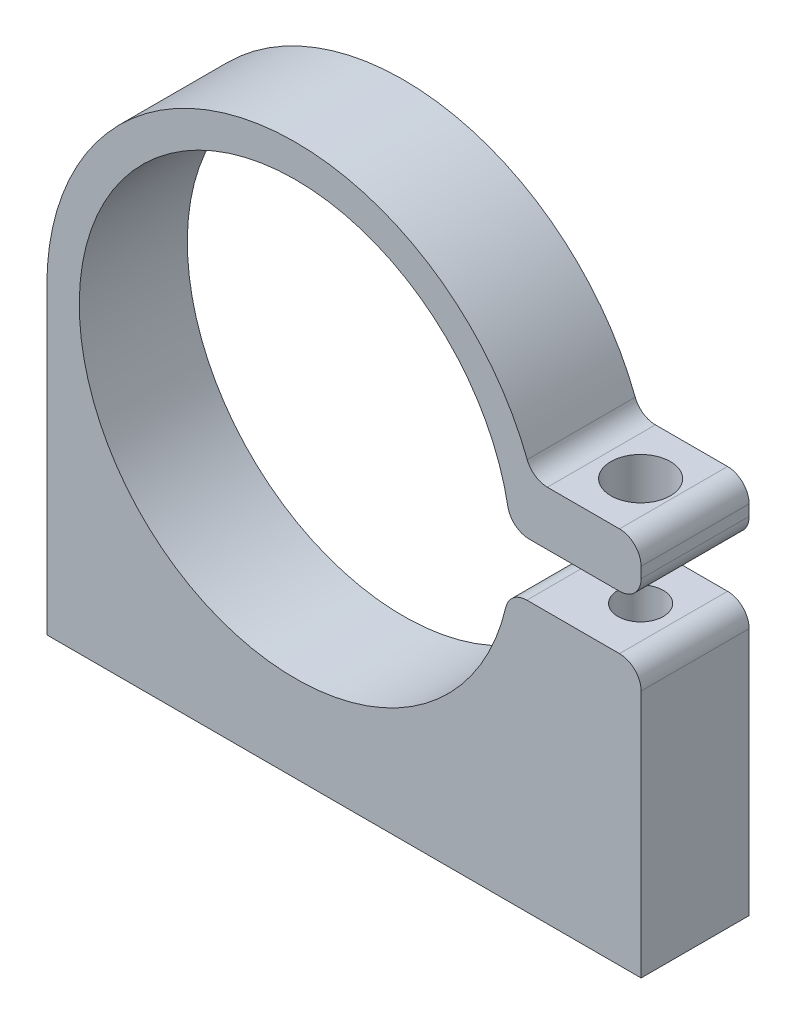
SolidWorks part; units mm, degrees
material "Сплав 2024"
ref_plane "Спереди" through (0, 0, 0) normal (0, 0, 1) x (1, 0, 0)
ref_plane "Сверху" through (0, 0, 0) normal (0, 1, 0) x (1, 0, 0)
ref_plane "Справа" through (0, 0, 0) normal (1, 0, 0) x (0, 0, -1)
sketch "Эскиз1" plane through (0, 0, 0) normal (0, 0, 1) x (1, 0, 0)
  line L0 (32, -3) -> (19.7737, -3)
  line L1 (19.8997, 2) -> (32, 2)
  line L2 (-23, 0) -> (-23, -28)
  line L3 (-23, -28) -> (32, -28)
  line L4 (32, -3) -> (32, -28)
  line L5 (32, 2) -> (32, 7)
  line L6 (32, 7) -> (21.9089, 7)
  arc A0 (19.8997, 2) -> (19.7737, -3) centre (0, 0) ccw
  arc A1 (21.9089, 7) -> (-23, 0) centre (0, 0) ccw
  circle A3 centre (0, 0) radius 23 construction
  circle A4 centre (0, 0) radius 20 construction
  point P4 (20.0824, 6.1398)
  point P12 (24, 0)
  dimension "D1" = 40
  dimension "D3" = 28
  dimension "D4" = 55
  dimension "D5" = 5
  dimension "D6" = 5
  dimension "D7" = 25
  dimension "D2" = 3
extrude "Бобышка-Вытянуть1" add sketch "Эскиз1" along normal blind 10
sketch "Эскиз2" plane through (0, 7, 0) normal (0, 1, 0) x (1, 0, 0)
  line L0 (26.9545, 0) -> (26.9545, -10) construction
  line L1 (32, -10) -> (32, 0) construction
  line L2 (32, -10) -> (21.9089, -10) construction
  line L3 (23.1247, -5) -> (32, -5) construction
fillet "Скругление1" radius 2 6 edges at (32, 2, 5) (32, 7, 5) (32, -3, 5) (19.7737, -3, 5) (19.8997, 2, 5) (21.9089, 7, 5)
hole_wizard "Отверстие с зазором M51" positions "Эскиз4" profile "Эскиз3" hole size "M5" standard "Ansi Metric"
sketch "Эскиз4" plane through (0, 7, 0) normal (0, 1, 0) x (1, 0, 0)
  line L0 (26.9545, 0) -> (26.9545, -10) construction
  point P0 (26.9545, -5)
sketch "Эскиз3" plane through (26.9545, 7, 5) normal (1, 0, 0) x (0, 0, 1)
  line L0 (0, 0) -> (0, 5)
  line L1 (0, 5) -> (2.75, 5)
  line L2 (2.75, 5) -> (2.75, 0)
  line L5 (2.75, 0) -> (0, 0)
  line L11 (0, -6.35) -> (0, 107.95) construction
  dimension "Диаметр сквозного отверстия" = 5.5
  dimension "Глубина сквозного отверстия" = 5
hole_wizard "Отверстие обработанное метчиком M5x0.81" positions "Эскиз6" profile "Эскиз5" tap size "M5x0.8" standard "Ansi Metric" end condition through all
sketch "Эскиз6" plane through (0, -3, 0) normal (0, 1, 0) x (1, 0, 0)
  line L0 (26.9545, 0) -> (26.9545, -10) construction
  point P0 (26.9545, -5)
sketch "Эскиз5" plane through (26.9545, -3, 5) normal (1, 0, 0) x (0, 0, 1)
  line L0 (0, 0) -> (0, 25)
  line L1 (0, 25) -> (2.1, 25)
  line L2 (2.1, 25) -> (2.1, 0)
  line L5 (2.1, 0) -> (0, 0)
  line L11 (0, -6.35) -> (0, 107.95) construction
  dimension "Диаметр проходного сверла" = 4.2
  dimension "Глубина проходного сверла" = 25
cosmetic thread "Отверстие резьбы1" parameters "D2"=5
sketch "Эскиз7" plane through (0, -28, 0) normal (0, -1, 0) x (1, 0, 0)
  line L0 (-23, 5) -> (3.4016, 5) construction
  line L1 (-23, 10) -> (-23, 0) construction
  line L2 (-15, 10) -> (-15, 0) construction
  line L3 (-23, 10) -> (32, 10) construction
  dimension "D1" = 8
hole_wizard "Отверстие обработанное метчиком M5x0.82" positions "Эскиз9" profile "Эскиз8" tap size "M5x0.8" standard "Ansi Metric"
sketch "Эскиз9" plane through (0, -28, 0) normal (0, -1, 0) x (-1, 0, 0)
  line L0 (15, -10) -> (15, 0) construction
  point P0 (15, -5)
sketch "Эскиз8" plane through (-15, -28, 5) normal (1, 0, 0) x (0, 0, -1)
  line L0 (0, 0) -> (0, 11.2618)
  line L1 (0, 11.2618) -> (2.1, 10)
  line L2 (2.1, 10) -> (2.1, 0)
  line L5 (2.1, 0) -> (0, 0)
  line L10 (0, 11.2618) -> (-2.1, 10) construction
  line L11 (0, -6.35) -> (0, 107.95) construction
  dimension "Диаметр сверла" = 4.2
  dimension "Глубина сверла" = 10
  dimension "Угол заточки сверла" = 118
cosmetic thread "Отверстие резьбы2" parameters "D1"=10, "D2"=5
